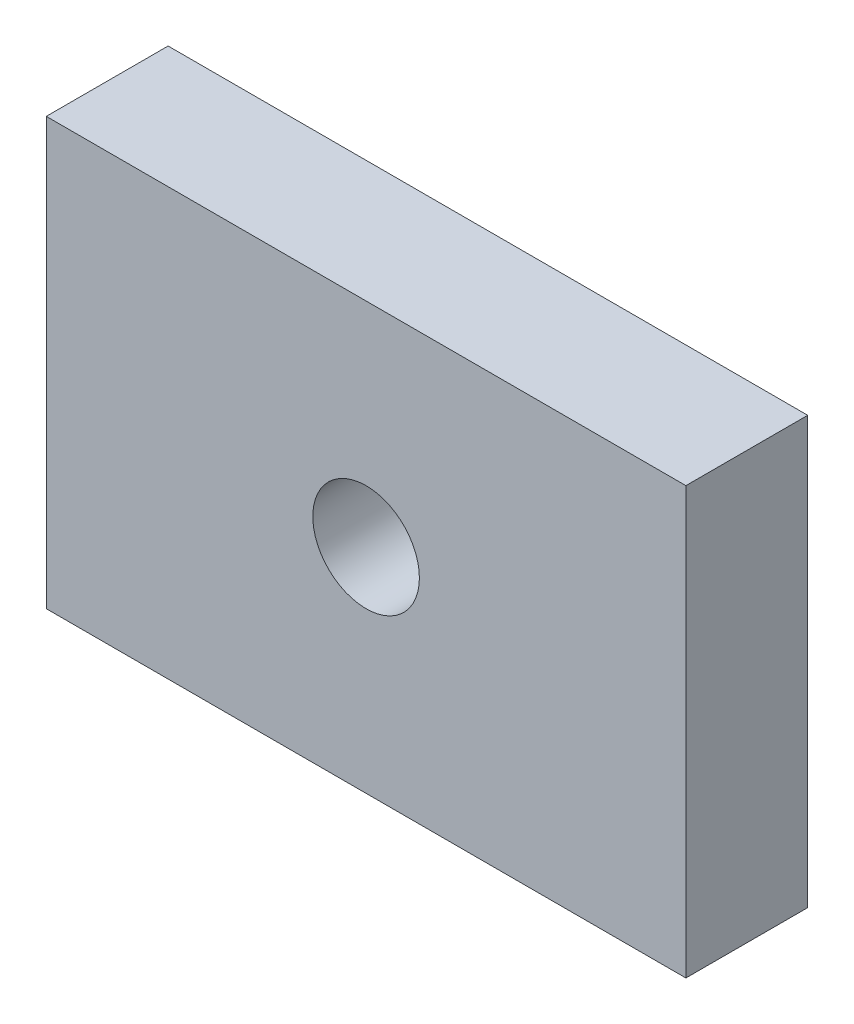
SolidWorks part; units mm, degrees
material "3.3547 (EN-AW 5083)"
ref_plane "Ebene vorne" through (0, 0, 0) normal (0, 0, 1) x (1, 0, 0)
ref_plane "Ebene oben" through (0, 0, 0) normal (0, 1, 0) x (1, 0, 0)
ref_plane "Ebene rechts" through (0, 0, 0) normal (1, 0, 0) x (0, 0, -1)
sketch "Skizze1" plane through (0, 0, 0) normal (0, 0, 1) x (1, 0, 0)
  line L1 (-20.3531, 13.8566) -> (21.6469, 13.8566)
  line L2 (-20.3531, 13.8566) -> (-20.3531, -14.1434)
  line L3 (-20.3531, -14.1434) -> (21.6469, -14.1434)
  line L4 (21.6469, 13.8566) -> (21.6469, -14.1434)
  circle A0 centre (0.6469, -0.1434) radius 3.5
  dimension "D3" = 14
  dimension "D4" = 21
  dimension "D1" = 42
  dimension "D2" = 28
extrude "Aufsatz-Linear austragen1" add sketch "Skizze1" along normal blind 8
sketch "Skizze2" plane through (-20.3531, 0, 0) normal (-1, 0, 0) x (0, 0, 1)
  line L0 (8, 13.8566) -> (0, 13.8566) construction
  line L1 (8, -14.1434) -> (0, -14.1434) construction
  circle A0 centre (4, 5.8566) radius 1.6
  circle A1 centre (4, -6.1434) radius 1.6
  dimension "D1" = 8
  dimension "D2" = 8
extrude "Schnitt-Linear austragen1" cut sketch "Skizze2" against normal blind 15
hole_wizard "M4 Gewindebohrung1" positions "3D-Skizze1" profile "Skizze3" tap size "M4" standard "DIN"
sketch3d "3D-Skizze1"
  line L0 (-5.3531, -6.1434, 4) -> (-20.3531, -6.1434, 4) construction
  line L1 (-5.3531, 5.8566, 4) -> (-20.3531, 5.8566, 4) construction
  point P0 (-20.3531, -6.1434, 4)
  point P4 (-20.3531, 5.8566, 4)
cosmetic thread "Bohrungsgewinde1"
cosmetic thread "Bohrungsgewinde2"
sketch "Skizze3" plane through (-20.3531, -6.1434, 4) normal (0, 1, 0) x (0, 0, 1)
  line L0 (0, 0) -> (0, 15.9914)
  line L1 (0, 15.9914) -> (1.65, 15)
  line L2 (1.65, 15) -> (1.65, 0)
  line L5 (1.65, 0) -> (0, 0)
  line L10 (0, 15.9914) -> (-1.65, 15) construction
  line L11 (0, -6.35) -> (0, 107.95) construction
  dimension "Bohrerdurchmesser" = 3.3
  dimension "Bohrungstiefe" = 15
  dimension "Spitzenwinkel" = 118
